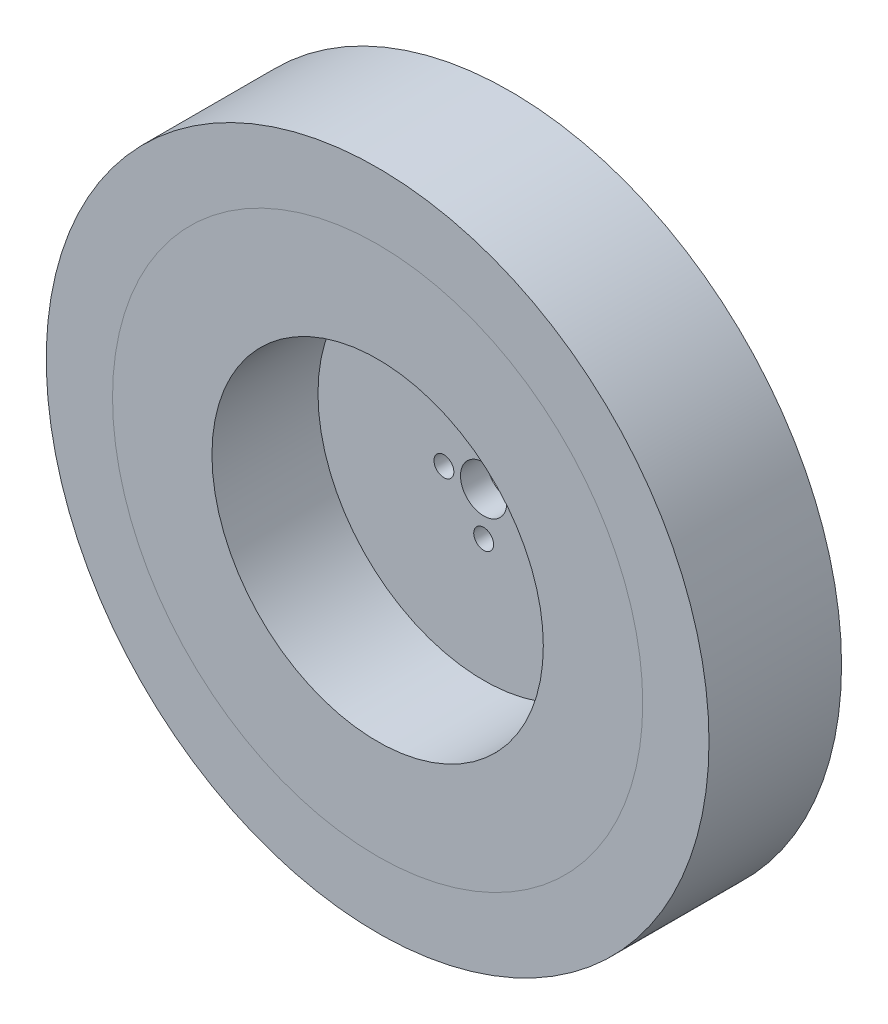
SolidWorks part; units mm, degrees
ref_plane "前视基准面" through (0, 0, 0) normal (0, 0, 1) x (1, 0, 0)
ref_plane "上视基准面" through (0, 0, 0) normal (0, 1, 0) x (1, 0, 0)
ref_plane "右视基准面" through (0, 0, 0) normal (1, 0, 0) x (0, 0, -1)
sketch "草图1" plane through (0, 0, 0) normal (0, 0, 1) x (1, 0, 0)
  circle A0 centre (0, 0) radius 50
  circle A1 centre (0, 0) radius 40
  dimension "D1" = 100
  dimension "D2" = 10
extrude "凸台-拉伸1" add sketch "草图1" along normal mid plane 20
sketch "草图3" plane through (0, 0, 0) normal (0, 0, 1) x (1, 0, 0)
  circle A0 centre (0, 0) radius 40
  circle A1 centre (0, 0) radius 37
  circle A2 centre (0, 0) radius 40 construction
  dimension "D1" = 3
extrude "凸台-拉伸2" add sketch "草图3" along normal mid plane 20 separate body
sketch "草图4" plane through (0, 0, -10) normal (0, 0, -1) x (-1, 0, 0)
  circle A0 centre (0, 0) radius 37
  circle A1 centre (0, 0) radius 37 construction
extrude "凸台-拉伸3" add sketch "草图4" against normal blind 4
sketch "草图5" plane through (0, 0, -6) normal (0, 0, 1) x (1, 0, 0)
  circle A0 centre (0, 0) radius 3.5
  circle A1 centre (0, 0) radius 6 construction
  circle A2 centre (0, 0) radius 6.5 construction
  circle A3 centre (0, 6.5) radius 1.5
  circle A4 centre (-6, 0) radius 1.5
  circle A5 centre (6, 0) radius 1.5
  circle A6 centre (0, -6.5) radius 1.5
  dimension "D1" = 7
  dimension "D2" = 12
  dimension "D3" = 13
  dimension "D4" = 3
extrude "切除-拉伸1" cut sketch "草图5" against normal through all
sketch "草图6" plane through (0, 0, -6) normal (0, 0, 1) x (1, 0, 0)
  circle A0 centre (0, 0) radius 25
  circle A1 centre (0, 0) radius 37 construction
  circle A2 centre (0, 0) radius 37
  dimension "D1" = 50
extrude "凸台-拉伸4" add sketch "草图6" along normal blind 16
